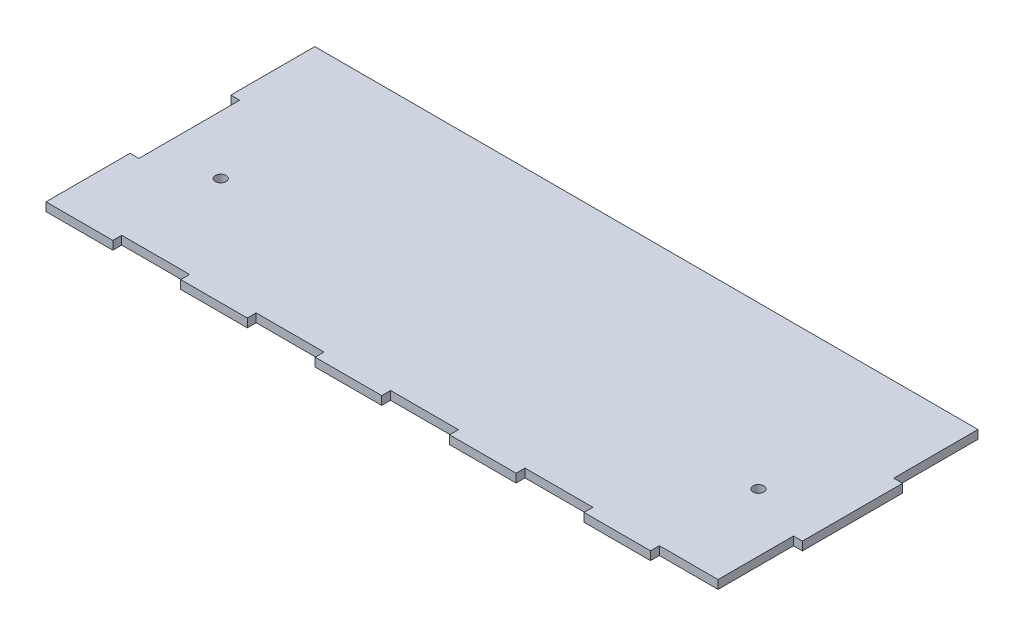
SolidWorks part; units mm, degrees
ref_plane "Front Plane" through (0, 0, 0) normal (0, 0, 1) x (1, 0, 0)
ref_plane "Top Plane" through (0, 0, 0) normal (0, 1, 0) x (1, 0, 0)
ref_plane "Right Plane" through (0, 0, 0) normal (1, 0, 0) x (0, 0, -1)
other "Default"
sketch "Sketch1" plane through (0, 0, 0) normal (0, 1, 0) x (1, 0, 0)
  line L1 (-250, -100) -> (250, -100)
  line L2 (-250, -100) -> (-250, 100)
  line L3 (-250, 100) -> (250, 100)
  line L4 (250, -100) -> (250, 100)
  line L5 (-250, -100) -> (250, 100) construction
  line L6 (-250, 100) -> (250, -100) construction
  point P0 (0, 0)
  dimension "D1" = 500
  dimension "D2" = 200
extrude "Boss-Extrude1" add sketch "Sketch1" along normal mid plane 6.35
sketch "Sketch2" plane through (0, 3.175, 0) normal (0, 1, 0) x (1, 0, 0)
  line L0 (-250, -100) -> (250, -100) construction
  line L1 (-200.25, -100) -> (-149.75, -100)
  line L2 (-200.25, -100) -> (-200.25, -93.4)
  line L3 (-200.25, -93.4) -> (-149.75, -93.4)
  line L4 (-149.75, -100) -> (-149.75, -93.4)
  point P10 (-175, -93.4)
  dimension "D1" = 6.6
  dimension "D2" = 50.5
  dimension "D3" = 75
extrude "Cut-Extrude1" cut sketch "Sketch2" against normal through all
pattern_linear "LPattern1" count 5 spacing 100 along (1, 0, 0) of "Cut-Extrude1"
sketch "Sketch3" plane through (0, 3.175, 0) normal (0, 1, 0) x (1, 0, 0)
  line L0 (-250, 100) -> (-250, -100) construction
  line L1 (250, -93.4) -> (243.4, -93.4)
  line L2 (250, -93.4) -> (250, -37.25)
  line L3 (250, -37.25) -> (243.4, -37.25)
  line L4 (243.4, -93.4) -> (243.4, -37.25)
  line L5 (250, 100) -> (243.4, 100)
  line L6 (250, 100) -> (250, 37.25)
  line L7 (250, 37.25) -> (243.4, 37.25)
  line L8 (243.4, 100) -> (243.4, 37.25)
  line L9 (-250, -37.5) -> (-243.4, -37.5)
  line L10 (-250, -37.5) -> (-250, 37.5)
  line L11 (-250, 37.5) -> (-243.4, 37.5)
  line L12 (-243.4, -37.5) -> (-243.4, 37.5)
  line L13 (-200.25, -93.4) -> (-200.25, -100) construction
  point P16 (-243.4, 0)
  dimension "D1" = 0.25
  dimension "D2" = 0.25
  dimension "D3" = 75
extrude "Cut-Extrude2" cut sketch "Sketch3" against normal through all
sketch "Sketch4" plane through (0, 3.175, 0) normal (0, 1, 0) x (1, 0, 0)
  line L0 (-200, -20) -> (200, -20) construction
  line L1 (243.4, 100) -> (-250, 100) construction
  circle A0 centre (-200, -20) radius 4
  circle A1 centre (200, -20) radius 4
  point P4 (0, -20)
  dimension "D2" = 8
  dimension "D1" = 400
  dimension "D3" = 120
extrude "Axle Holes" cut sketch "Sketch4" against normal through all
sketch "Sketch5" [suppressed] plane through (0, 3.175, 0) normal (0, 1, 0) x (1, 0, 0)
  line L0 (-200, -30) -> (200, -30) construction
  line L1 (243.4, 100) -> (-250, 100) construction
  circle A0 centre (-200, -30) radius 7
  circle A1 centre (200, -30) radius 7
  point P4 (0, -30)
  dimension "D2" = 14
  dimension "D1" = 133.5
  dimension "D3" = 450
extrude "Cross Axle Holes" [suppressed] cut sketch "Sketch5" against normal through all
